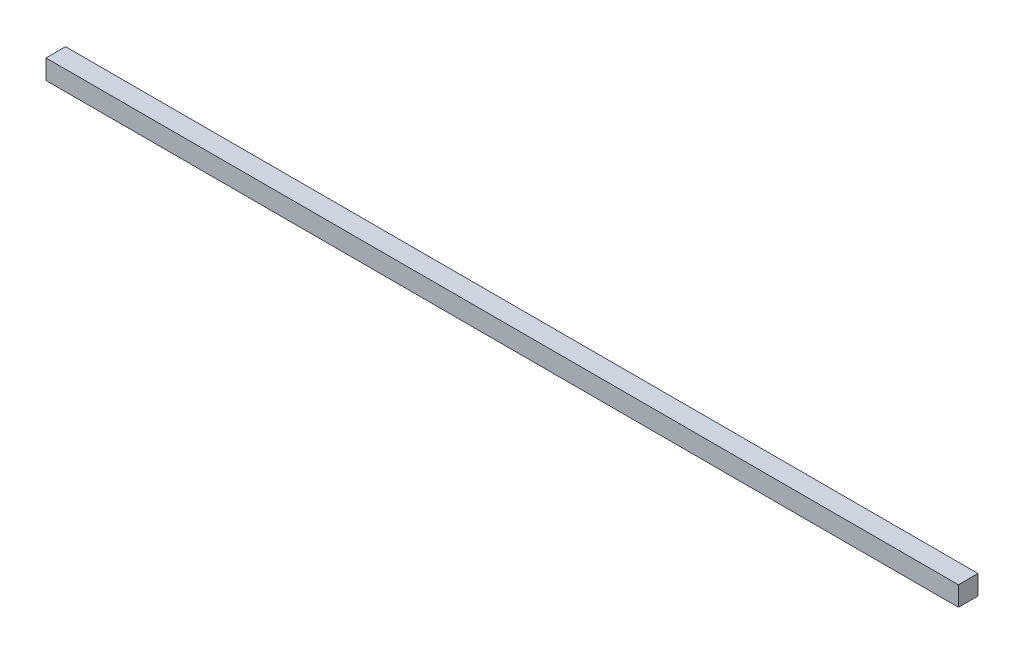
SolidWorks part; units mm, degrees
material "Oak"
ref_plane "Front" through (0, 0, 0) normal (0, 0, 1) x (1, 0, 0)
ref_plane "Top" through (0, 0, 0) normal (0, 1, 0) x (1, 0, 0)
ref_plane "Right" through (0, 0, 0) normal (1, 0, 0) x (0, 0, -1)
sketch "Sketch1" plane through (0, 0, 0) normal (0, 0, 1) x (1, 0, 0)
  line L1 (0, 0) -> (4150, 0)
  line L2 (0, 0) -> (0, 88.9)
  line L3 (0, 88.9) -> (4150, 88.9)
  line L4 (4150, 0) -> (4150, 88.9)
  dimension "D1" = 4150
  dimension "D2" = 88.9
extrude "Boss-Extrude1" add sketch "Sketch1" along normal blind 88.9
